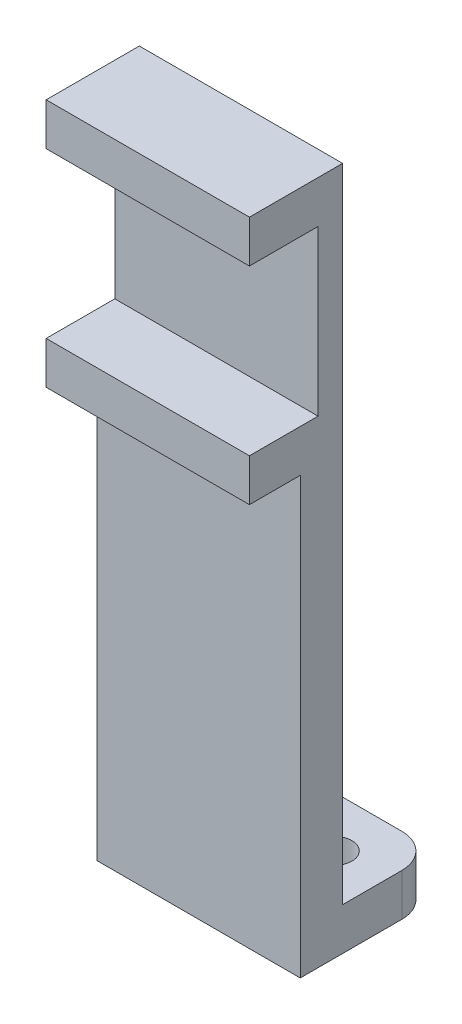
SolidWorks part; units mm, degrees
ref_plane "Front Plane" through (0, 0, 0) normal (0, 0, 1) x (1, 0, 0)
ref_plane "Top Plane" through (0, 0, 0) normal (0, 1, 0) x (1, 0, 0)
ref_plane "Right Plane" through (0, 0, 0) normal (1, 0, 0) x (0, 0, -1)
sketch "Sketch1" plane through (0, 0, 0) normal (0, 1, 0) x (1, 0, 0)
  line L1 (-6, -4) -> (6, -4)
  line L2 (-6, -4) -> (-6, 4)
  line L3 (-6, 4) -> (6, 4)
  line L4 (6, -4) -> (6, 4)
  line L5 (-6, -4) -> (6, 4) construction
  line L6 (-6, 4) -> (6, -4) construction
  point P0 (0, 0)
  dimension "D1" = 8
  dimension "D2" = 12
extrude "Boss-Extrude1" add sketch "Sketch1" along normal blind 2.5
fillet "Fillet1" radius 2 2 edges at (-6, 1.25, -4) (6, 1.25, -4)
sketch "Sketch2" plane through (0, 2.5, 0) normal (0, 1, 0) x (1, 0, 0)
  line L0 (-6, -4) -> (6, -4) construction
  line L1 (6, -4) -> (6, 2) construction
  line L2 (-6, 2) -> (-6, -4) construction
  circle A0 centre (3, 1) radius 1.05
  circle A1 centre (-3, 1) radius 1.05
  dimension "D1" = 2.1
  dimension "D2" = 2.1
  dimension "D4" = 5
  dimension "D5" = 3
  dimension "D3" = 5
  dimension "D6" = 3
extrude "Cut-Extrude1" cut sketch "Sketch2" against normal blind 2.5
sketch "Sketch3" plane through (0, 2.5, 0) normal (0, 1, 0) x (1, 0, 0)
  line L0 (6, -4) -> (6, 2) construction
  line L1 (-6, -4) -> (6, -4)
  line L2 (-6, -4) -> (-6, -1.5)
  line L3 (-6, -1.5) -> (6, -1.5)
  line L4 (6, -4) -> (6, -1.5)
  dimension "D1" = 2.5
extrude "Boss-Extrude2" add sketch "Sketch3" along normal blind 37.9
sketch "Sketch5" plane through (0, 0, 4) normal (0, 0, 1) x (1, 0, 0)
  line L0 (6, 40.4) -> (6, 0) construction
  line L1 (-6, 40.4) -> (6, 40.4)
  line L2 (-6, 40.4) -> (-6, 37.9)
  line L3 (-6, 37.9) -> (6, 37.9)
  line L4 (6, 40.4) -> (6, 37.9)
  dimension "D1" = 2.5
extrude "Boss-Extrude4" add sketch "Sketch5" along normal blind 3
sketch "Sketch6" plane through (0, 0, 4) normal (0, 0, 1) x (1, 0, 0)
  line L0 (-6, 37.9) -> (-6, 0) construction
  line L1 (-6, 28.2) -> (6, 28.2)
  line L2 (-6, 28.2) -> (-6, 25.7)
  line L3 (-6, 25.7) -> (6, 25.7)
  line L4 (6, 28.2) -> (6, 25.7)
  line L5 (6, 37.9) -> (6, 0) construction
  line L6 (-6, 37.9) -> (6, 37.9) construction
  dimension "D1" = 9.7
  dimension "D2" = 2.5
extrude "Boss-Extrude5" add sketch "Sketch6" along normal blind 3
sketch "Sketch7" plane through (-6, 0, 0) normal (-1, 0, 0) x (0, 0, 1)
  line L1 (4, 37.9) -> (2.95, 37.9)
  line L2 (4, 37.9) -> (4, 28.2)
  line L3 (4, 28.2) -> (2.95, 28.2)
  line L4 (2.95, 37.9) -> (2.95, 28.2)
  dimension "D1" = 1.05
extrude "Cut-Extrude2" cut sketch "Sketch7" against normal blind 15
